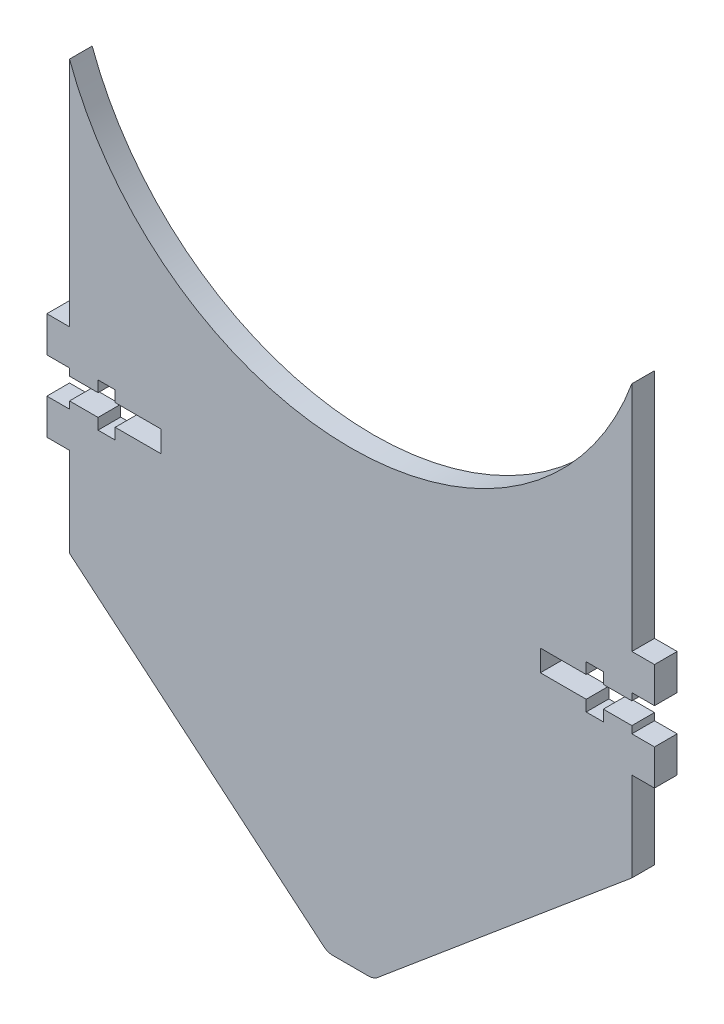
SolidWorks part; units mm, degrees
ref_plane "前视基准面" through (0, 0, 0) normal (0, 0, 1) x (1, 0, 0)
ref_plane "上视基准面" through (0, 0, 0) normal (0, 1, 0) x (1, 0, 0)
ref_plane "右视基准面" through (0, 0, 0) normal (1, 0, 0) x (0, 0, -1)
sketch "Sketch1" plane through (0, 0, 0) normal (0, 0, 1) x (1, 0, 0)
  line L0 (0, -85.8717) -> (0, 49.7374) construction
  line L2 (39.415, -20) -> (39.415, 40)
  line L4 (-39.415, -20) -> (-39.415, 40)
  line L6 (-3.7856, -49.8966) -> (-39.415, -20)
  line L8 (3.7856, -49.8966) -> (39.415, -20)
  line L9 (-39.415, 40) -> (39.415, 40) construction
  line L10 (2.5, -50.3645) -> (-2.5, -50.3645)
  arc A0 (39.415, 40) -> (-39.415, 40) centre (0, 54.5072) cw
  arc A3 (-3.7856, -49.8966) -> (-2.5, -50.3645) centre (-2.5, -48.3645) ccw
  arc A4 (3.7856, -49.8966) -> (2.5, -50.3645) centre (2.5, -48.3645) cw
  point P17 (0, -50.3645)
  dimension "D2" = 5
  dimension "D6" = 42
  dimension "D7" = 2
  dimension "D1" = 78.83
  dimension "D3" = 130
  dimension "D4" = 60
  dimension "D5" = 20
extrude "Boss-Extrude1" add sketch "Sketch1" along normal blind 3.175
sketch "Sketch2" plane through (0, 0, 3.175) normal (0, 0, 1) x (1, 0, 0)
  line L0 (-41.5791, 0) -> (41.497, 0) construction
  line L1 (0, 0) -> (0, 24.816) construction
  line L2 (39.415, -2.5) -> (39.415, -7.5)
  line L3 (39.415, -20) -> (39.415, 40) construction
  line L4 (39.415, -7.5) -> (42.59, -7.5)
  line L5 (42.59, -7.5) -> (42.59, -2.5)
  line L6 (42.59, -2.5) -> (39.415, -2.5)
  line L7 (39.415, -5) -> (51.6041, -5) construction
  line L8 (42.59, 2.5) -> (39.415, 2.5)
  line L9 (42.59, 7.5) -> (42.59, 2.5)
  line L10 (39.415, 7.5) -> (42.59, 7.5)
  line L11 (39.415, 2.5) -> (39.415, 7.5)
  line L12 (-39.415, -5) -> (-51.6041, -5) construction
  line L13 (-39.415, 2.5) -> (-39.415, 7.5)
  line L14 (-39.415, 7.5) -> (-42.59, 7.5)
  line L15 (-42.59, 7.5) -> (-42.59, 2.5)
  line L16 (-42.59, 2.5) -> (-39.415, 2.5)
  line L17 (-42.59, -2.5) -> (-39.415, -2.5)
  line L18 (-42.59, -7.5) -> (-42.59, -2.5)
  line L19 (-39.415, -7.5) -> (-42.59, -7.5)
  line L20 (-39.415, -2.5) -> (-39.415, -7.5)
  dimension "D1" = 5
  dimension "D2" = 3.175
  dimension "D3" = 5
extrude "Boss-Extrude2" add sketch "Sketch2" against normal blind 3.175
sketch "Sketch3" plane through (0, 0, 3.175) normal (0, 0, 1) x (1, 0, 0)
  line L0 (-43.1526, 0) -> (45.3724, 0) construction
  line L1 (39.415, 1.5) -> (35.415, 1.5)
  line L2 (39.415, 7.5) -> (39.415, 40) construction
  line L3 (35.415, 1.5) -> (35.415, 3.05)
  line L4 (35.415, 3.05) -> (33.015, 3.05)
  line L5 (33.015, 3.05) -> (33.015, 1.5)
  line L6 (33.015, 1.5) -> (26.59, 1.5)
  line L7 (39.415, 1.5) -> (39.415, -1.5)
  line L8 (26.59, 1.5) -> (26.59, -1.5)
  line L9 (33.015, -1.5) -> (26.59, -1.5)
  line L10 (33.015, -3.05) -> (33.015, -1.5)
  line L11 (35.415, -3.05) -> (33.015, -3.05)
  line L12 (35.415, -1.5) -> (35.415, -3.05)
  line L13 (39.415, -1.5) -> (35.415, -1.5)
  line L14 (42.59, -7.5) -> (42.59, -2.5) construction
  line L15 (0, 0) -> (0, 9.8166) construction
  line L16 (-39.415, -1.5) -> (-35.415, -1.5)
  line L17 (-35.415, -1.5) -> (-35.415, -3.05)
  line L18 (-35.415, -3.05) -> (-33.015, -3.05)
  line L19 (-33.015, -3.05) -> (-33.015, -1.5)
  line L20 (-33.015, -1.5) -> (-26.59, -1.5)
  line L21 (-26.59, 1.5) -> (-26.59, -1.5)
  line L22 (-39.415, 1.5) -> (-39.415, -1.5)
  line L23 (-33.015, 1.5) -> (-26.59, 1.5)
  line L24 (-33.015, 3.05) -> (-33.015, 1.5)
  line L25 (-35.415, 3.05) -> (-33.015, 3.05)
  line L26 (-35.415, 1.5) -> (-35.415, 3.05)
  line L27 (-39.415, 1.5) -> (-35.415, 1.5)
  point P14 (26.59, 0)
  point P15 (39.415, 0)
  point P35 (-39.415, 0)
  point P36 (-26.59, 0)
  dimension "D1" = 6.1
  dimension "D2" = 3
  dimension "D3" = 2.4
  dimension "D4" = 16
  dimension "D5" = 4
extrude "Cut-Extrude1" cut sketch "Sketch3" against normal through all
